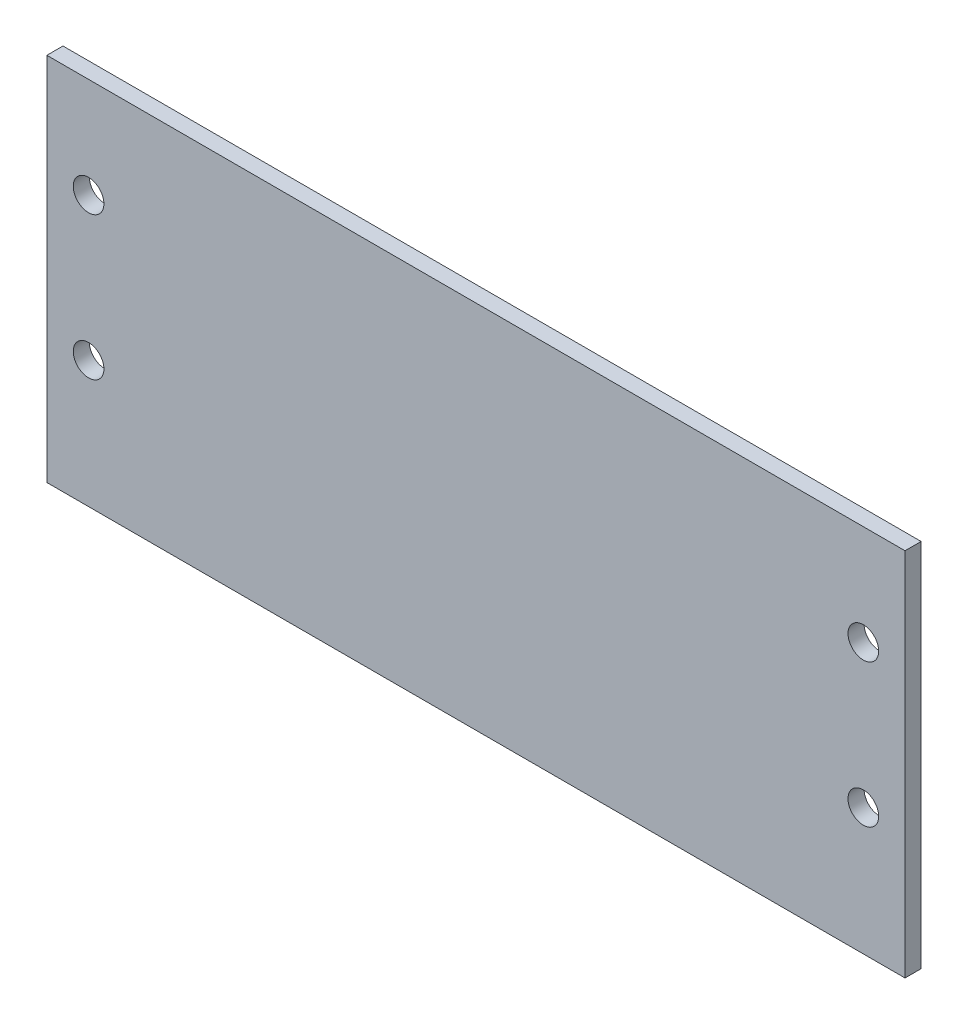
SolidWorks part; units mm, degrees
ref_plane "Front Plane" through (0, 0, 0) normal (0, 0, 1) x (1, 0, 0)
ref_plane "Top Plane" through (0, 0, 0) normal (0, 1, 0) x (1, 0, 0)
ref_plane "Right Plane" through (0, 0, 0) normal (1, 0, 0) x (0, 0, -1)
sketch "Sketch1" plane through (0, 0, 0) normal (0, 0, 1) x (1, 0, 0)
  line L1 (-274.9879, 130.6503) -> (258.4121, 130.6503)
  line L2 (-274.9879, 130.6503) -> (-274.9879, -99.3497)
  line L3 (-274.9879, -99.3497) -> (258.4121, -99.3497)
  line L4 (258.4121, 130.6503) -> (258.4121, -99.3497)
  dimension "D1" = 533.4
  dimension "D2" = 230
extrude "Boss-Extrude1" add sketch "Sketch1" along normal blind 10
sketch "Sketch2" plane through (0, 0, 10) normal (0, 0, 1) x (1, 0, 0)
  circle A0 centre (232.5041, 68.3723) radius 9.525
  circle A1 centre (232.5041, -20.5277) radius 9.525
  circle A2 centre (-249.0799, 68.3723) radius 9.525
  circle A3 centre (-249.0799, -20.5277) radius 9.525
extrude "Cut-Extrude1" cut sketch "Sketch2" against normal blind 10
